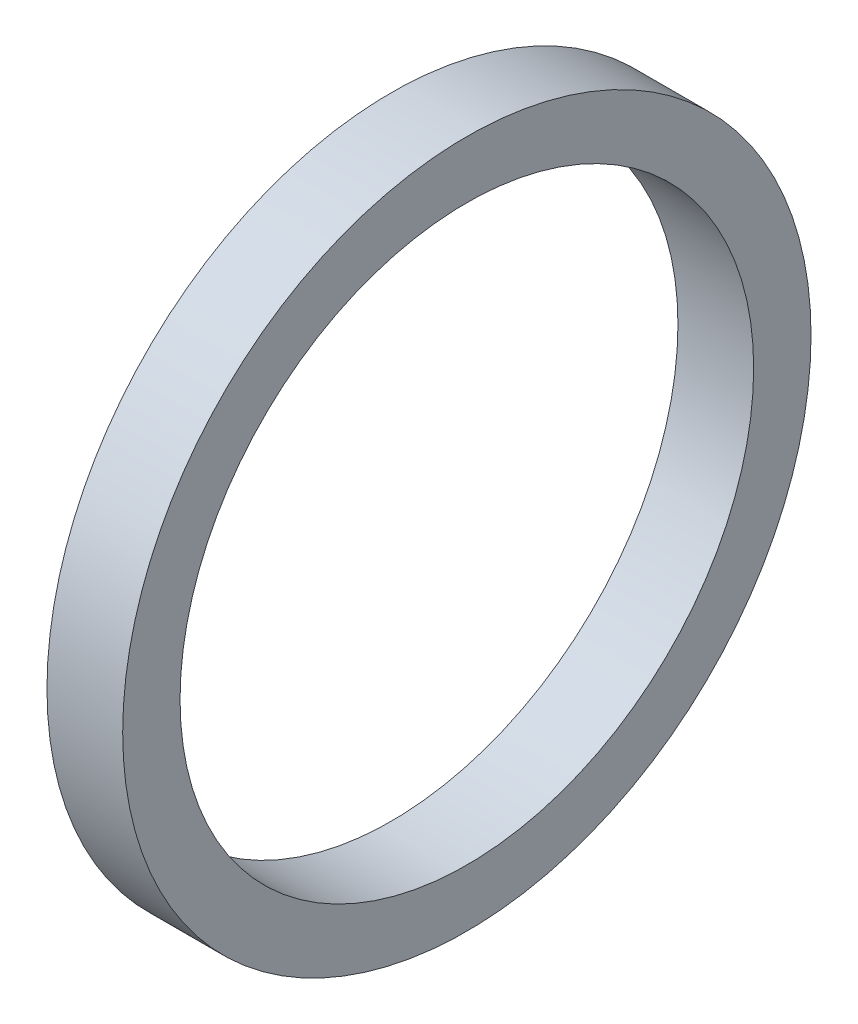
SolidWorks part; units mm, degrees
material "AISI 1020 Steel, Cold Rolled"
ref_plane "Front Plane" through (0, 0, 0) normal (0, 0, 1) x (1, 0, 0)
ref_plane "Top Plane" through (0, 0, 0) normal (0, 1, 0) x (1, 0, 0)
ref_plane "Right Plane" through (0, 0, 0) normal (1, 0, 0) x (0, 0, -1)
sketch "Sketch1" plane through (0, 0, 0) normal (1, 0, 0) x (0, 0, -1)
  circle A0 centre (0, 0) radius 7.9375
  circle A1 centre (0, 0) radius 9.525
  dimension "D1" = 15.875
  dimension "D2" = 19.05
extrude "Boss-Extrude1" add sketch "Sketch1" along normal blind 2.0955
